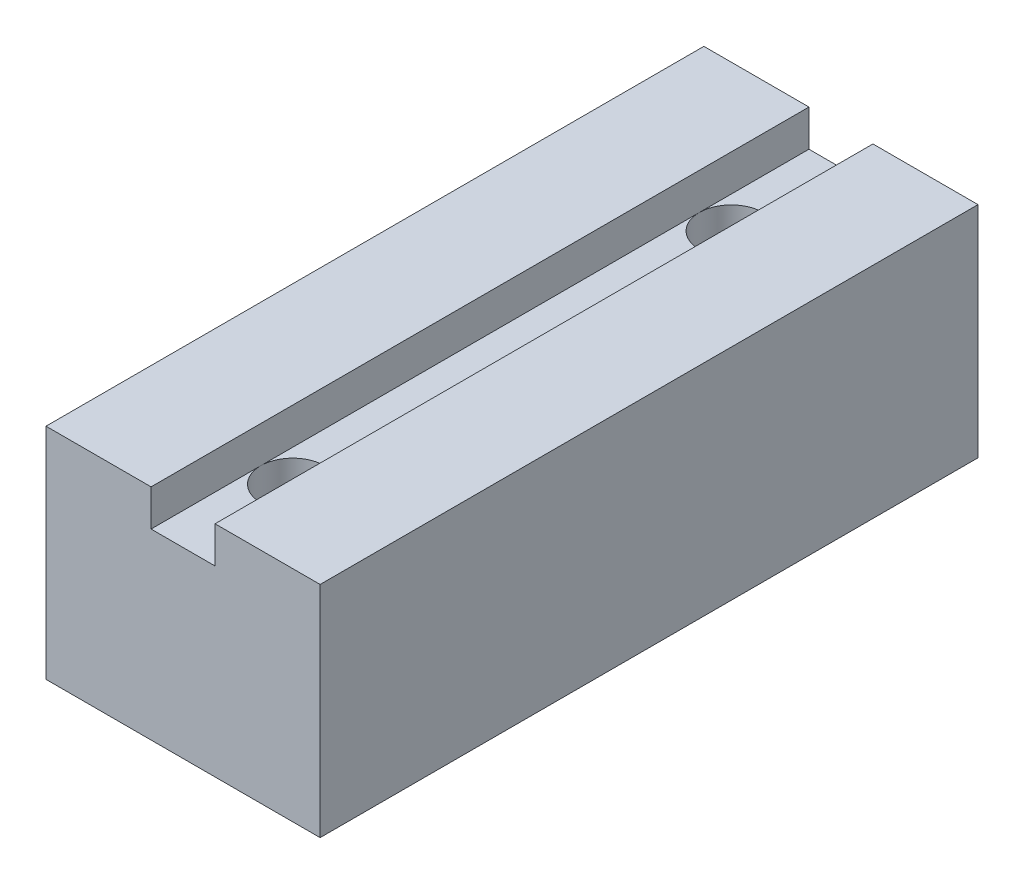
SolidWorks part; units mm, degrees
ref_plane "Front" through (0, 0, 0) normal (0, 0, 1) x (1, 0, 0)
ref_plane "Top" through (0, 0, 0) normal (0, 1, 0) x (1, 0, 0)
ref_plane "Right" through (0, 0, 0) normal (1, 0, 0) x (0, 0, -1)
sketch "Sketch1" plane through (0, 0, 0) normal (0, 1, 0) x (1, 0, 0)
  line L1 (0, 0) -> (15, 0)
  line L2 (0, 0) -> (0, 36)
  line L3 (0, 36) -> (15, 36)
  line L4 (15, 0) -> (15, 36)
  dimension "D1" = 15
  dimension "D2" = 36
extrude "Boss-Extrude1" add sketch "Sketch1" along normal blind 12
sketch "Sketch2" plane through (0, 12, 0) normal (0, 1, 0) x (1, 0, 0)
  line L0 (0, 18) -> (15, 18)
  line L1 (0, 36) -> (0, 0) construction
  line L2 (15, 0) -> (15, 36) construction
  line L3 (7.5, 30) -> (7.5, 6)
  circle A0 centre (7.5, 30) radius 1.75
  circle A2 centre (7.5, 6) radius 1.75
  point P9 (7.5, 18)
  dimension "D1" = 24
extrude "Cut-Extrude1" cut sketch "Sketch2" against normal blind 12 contours A0 | A2
sketch "Sketch3" plane through (0, 12, 0) normal (0, 1, 0) x (1, 0, 0)
  line L0 (5.75, 0) -> (9.25, 0)
  line L1 (5.75, 0) -> (5.75, 36)
  line L2 (9.25, 0) -> (9.25, 36)
  line L3 (5.75, 36) -> (9.25, 36)
  line L4 (0, 0) -> (15, 0) construction
  line L5 (0, 36) -> (0, 0) construction
  point P6 (7.5, 36)
  dimension "D1" = 36
  dimension "D2" = 3.5
  dimension "D3" = 7.5
extrude "Cut-Extrude2" cut sketch "Sketch3" against normal blind 2
